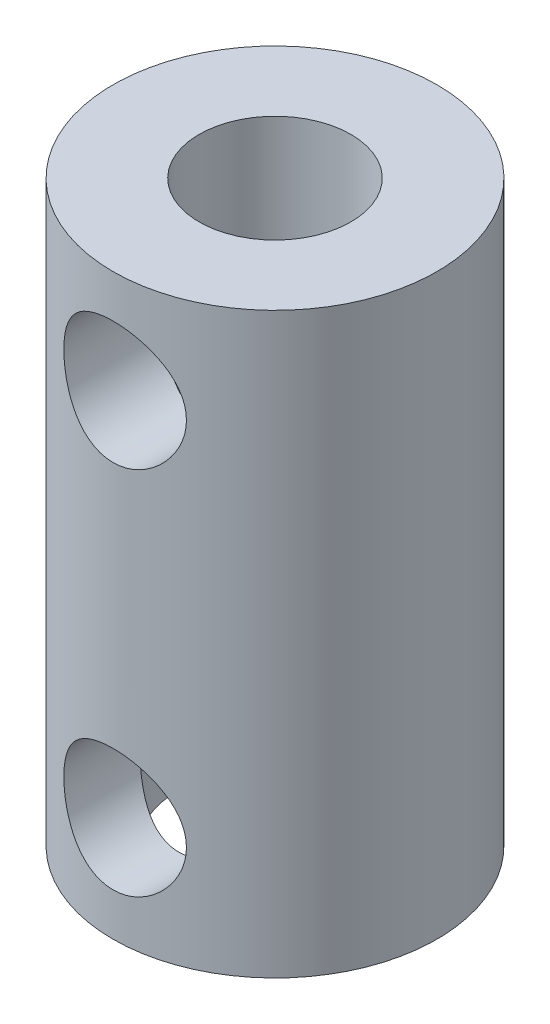
SolidWorks part; units mm, degrees
ref_plane "Front Plane" through (0, 0, 0) normal (0, 0, 1) x (1, 0, 0)
ref_plane "Top Plane" through (0, 0, 0) normal (0, 1, 0) x (1, 0, 0)
ref_plane "Right Plane" through (0, 0, 0) normal (1, 0, 0) x (0, 0, -1)
sketch "Sketch1" plane through (0, 0, 0) normal (0, 0, 1) x (1, 0, 0)
  line L0 (5.334, 19.05) -> (0, 19.05)
  line L1 (0, 19.05) -> (0, 0)
  line L2 (0, 0) -> (5.334, 0)
  line L3 (5.334, 0) -> (5.334, 19.05)
  line L4 (0, 19.05) -> (0, 0) construction
revolve "Revolve1" add sketch "Sketch1" angle 360 about L4
hole_wizard "CSK for #10 Flat Head Machine Screw (100)1" positions "Sketch3" profile "Sketch2" countersink size "#10" standard "ANSI Inch"
sketch "Sketch3" plane through (0, 0, 0) normal (0, -1, 0) x (-1, 0, 0)
  point P0 (0, 0)
sketch "Sketch2" plane through (0, 0, 0) normal (1, 0, 0) x (0, 0, -1)
  line L0 (0, 0) -> (0, 19.05)
  line L1 (0, 19.05) -> (2.5, 19.05)
  line L2 (2.5, 19.05) -> (2.5, 9.9306)
  line L3 (2.5, 9.9306) -> (3.175, 9.525)
  line L4 (3.175, 9.525) -> (3.175, 0)
  line L6 (3.175, 0) -> (0, 0)
  line L7 (-2.5, 9.9306) -> (-3.175, 9.525) construction
  line L11 (0, -6.35) -> (0, 107.95) construction
  dimension "Thru Hole Dia." = 5
  dimension "Thru Hole Depth" = 19.05
  dimension "C'Sink Dia." = 6.35
  dimension "C'Sink Angle" = 118
  dimension "Head Clearance" = 9.525
hole_wizard "#21 (0.159) Diameter Hole1" positions "3DSketch1" profile "Sketch4" hole size "#21" standard "ANSI Inch"
sketch3d "3DSketch1"
  point P0 (0, 15.621, 5.334)
sketch "Sketch4" plane through (0, 15.621, 5.334) normal (1, 0, 0) x (0, -1, 0)
  line L0 (0, 0) -> (0, 2.834)
  line L1 (0, 2.834) -> (2.0193, 2.834)
  line L2 (2.0193, 2.834) -> (2.0193, 0)
  line L5 (2.0193, 0) -> (0, 0)
  line L11 (0, -6.35) -> (0, 107.95) construction
  dimension "Thru Hole Dia." = 4.0386
  dimension "Thru Hole Depth" = 2.834
hole_wizard "#21 (0.159) Diameter Hole2" positions "3DSketch2" profile "Sketch5" hole size "#21" standard "ANSI Inch"
sketch3d "3DSketch2"
  point P0 (0, 3.429, 5.334)
sketch "Sketch5" plane through (0, 3.429, 5.334) normal (1, 0, 0) x (0, -1, 0)
  line L0 (0, 0) -> (0, 2.159)
  line L1 (0, 2.159) -> (2.0193, 2.159)
  line L2 (2.0193, 2.159) -> (2.0193, 0)
  line L5 (2.0193, 0) -> (0, 0)
  line L11 (0, -6.35) -> (0, 107.95) construction
  dimension "Thru Hole Dia." = 4.0386
  dimension "Thru Hole Depth" = 2.159
